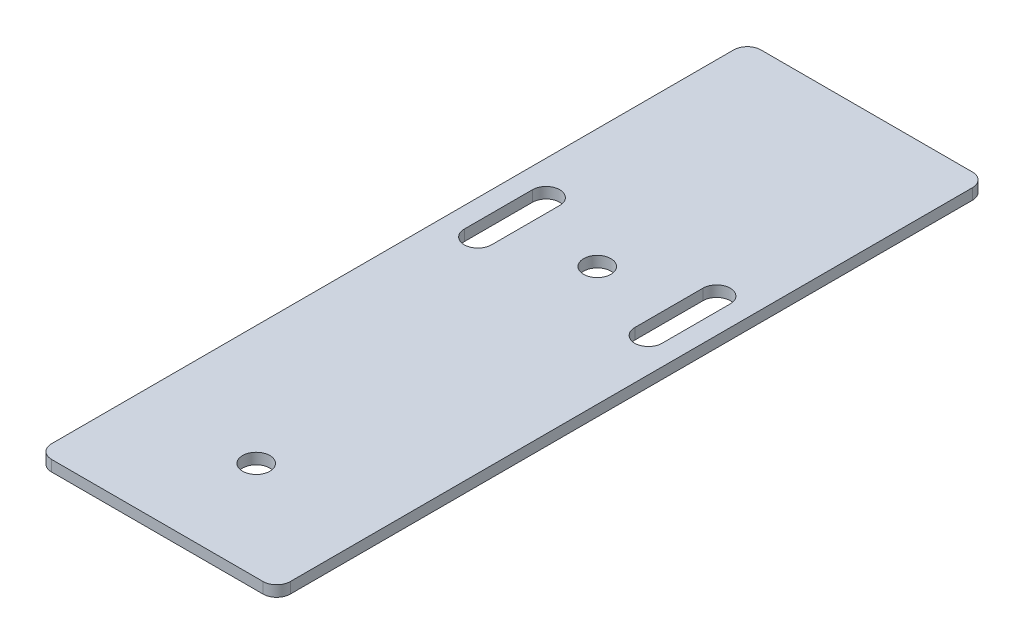
SolidWorks part; units mm, degrees
ref_plane "前视基准面" through (0, 0, 0) normal (0, 0, 1) x (1, 0, 0)
ref_plane "上视基准面" through (0, 0, 0) normal (0, 1, 0) x (1, 0, 0)
ref_plane "右视基准面" through (0, 0, 0) normal (1, 0, 0) x (0, 0, -1)
sketch "草图1" plane through (0, 0, 0) normal (0, 1, 0) x (1, 0, 0)
  line L1 (-17.5, 52) -> (17.5, 52)
  line L2 (-17.5, 52) -> (-17.5, -52)
  line L3 (-17.5, -52) -> (17.5, -52)
  line L4 (17.5, 52) -> (17.5, -52)
  line L5 (-17.5, 52) -> (17.5, -52) construction
  line L6 (-17.5, -52) -> (17.5, 52) construction
  point P0 (0, 0)
  dimension "D1" = 35
  dimension "D2" = 104
extrude "凸台-拉伸1" add sketch "草图1" along normal blind 1.6
sketch "草图3" plane through (0, 1.6, 0) normal (0, 1, 0) x (1, 0, 0)
  line L0 (0, 52) -> (0, -52) construction
  line L1 (17.5, 52) -> (-17.5, 52) construction
  line L2 (-17.5, -52) -> (17.5, -52) construction
  circle A1 centre (0, 12.5) radius 2
  circle A3 centre (0, -37.5) radius 2
  dimension "D2" = 4
  dimension "D3" = 4
  dimension "D1" = 12.5
  dimension "D4" = 37.5
extrude "切除-拉伸1" cut sketch "草图3" against normal through all
sketch "草图4" plane through (0, 1.6, 0) normal (0, 1, 0) x (1, 0, 0)
  line L0 (0, 12.5) -> (17.5, 12.5) construction
  line L1 (17.5, -52) -> (17.5, 52) construction
  line L2 (12.5, 7.5) -> (12.5, 17.5) construction
  line L3 (10.5, 7.5) -> (10.5, 17.5)
  line L4 (14.5, 7.5) -> (14.5, 17.5)
  line L5 (0, -0.88) -> (0, 0.88) construction
  line L6 (-12.5, 7.5) -> (-12.5, 17.5) construction
  line L7 (-10.5, 7.5) -> (-10.5, 17.5)
  line L8 (-14.5, 7.5) -> (-14.5, 17.5)
  arc A0 (10.5, 7.5) -> (14.5, 7.5) centre (12.5, 7.5) ccw
  arc A1 (14.5, 17.5) -> (10.5, 17.5) centre (12.5, 17.5) ccw
  arc A2 (-10.5, 7.5) -> (-14.5, 7.5) centre (-12.5, 7.5) cw
  arc A3 (-14.5, 17.5) -> (-10.5, 17.5) centre (-12.5, 17.5) cw
  point P7 (12.5, 12.5)
  point P16 (-12.5, 12.5)
  dimension "D3" = 2
  dimension "D1" = 12.5
  dimension "D2" = 10
extrude "切除-拉伸2" cut sketch "草图4" against normal through all
fillet "圆角1" radius 2 4 edges at (-17.5, 0.8, -52) (17.5, 0.8, -52) (17.5, 0.8, 52) (-17.5, 0.8, 52)
